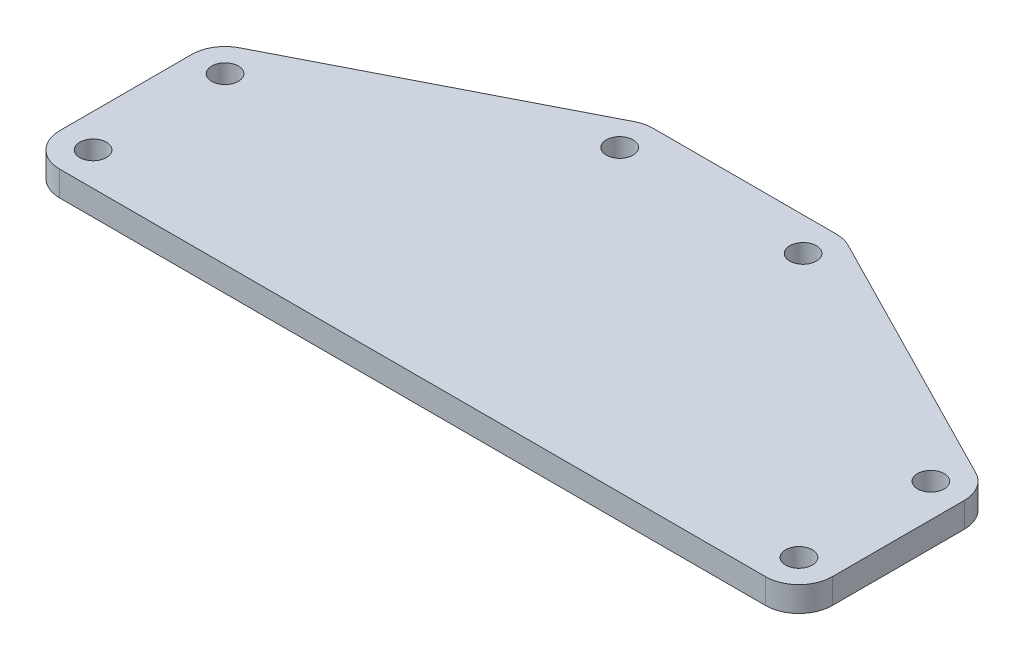
SolidWorks part; units mm, degrees
ref_plane "Front Plane" through (0, 0, 0) normal (0, 0, 1) x (1, 0, 0)
ref_plane "Top Plane" through (0, 0, 0) normal (0, 1, 0) x (1, 0, 0)
ref_plane "Right Plane" through (0, 0, 0) normal (1, 0, 0) x (0, 0, -1)
sketch "Sketch1" plane through (0, 0, 0) normal (0, 1, 0) x (1, 0, 0)
  line L0 (0, 0) -> (0, 20.4742) construction
  line L1 (-42.325, -31.825) -> (-42.325, -16) construction
  line L2 (11, 0) -> (-11, 0) construction
  line L3 (-46.325, -31.825) -> (-46.325, -16)
  line L4 (-44.1445, -12.4378) -> (-12.8195, 3.5622)
  line L5 (44.1445, -12.4378) -> (12.8195, 3.5622)
  line L6 (46.325, -31.825) -> (46.325, -16)
  line L7 (-11, 4) -> (11, 4)
  line L8 (-42.325, -35.825) -> (42.325, -35.825)
  circle A0 centre (-42.325, -31.825) radius 1.6
  circle A1 centre (-42.325, -16) radius 1.6
  circle A2 centre (42.325, -31.825) radius 1.6
  circle A3 centre (42.325, -16) radius 1.6
  circle A4 centre (-11, 0) radius 1.6
  circle A5 centre (11, 0) radius 1.6
  arc A6 (-11, 4) -> (-12.8195, 3.5622) centre (-11, 0) ccw
  arc A7 (-44.1445, -12.4378) -> (-46.325, -16) centre (-42.325, -16) ccw
  arc A8 (-46.325, -31.825) -> (-42.325, -35.825) centre (-42.325, -31.825) ccw
  arc A9 (46.325, -31.825) -> (42.325, -35.825) centre (42.325, -31.825) cw
  arc A10 (44.1445, -12.4378) -> (46.325, -16) centre (42.325, -16) cw
  arc A11 (11, 4) -> (12.8195, 3.5622) centre (11, 0) cw
  point P15 (0, 0)
  dimension "D1" = 3.2
  dimension "D6" = 4
  dimension "D2" = 15.825
  dimension "D3" = 84.65
  dimension "D4" = 22
  dimension "D5" = 35.1746
extrude "Boss-Extrude1" add sketch "Sketch1" along normal blind 3
